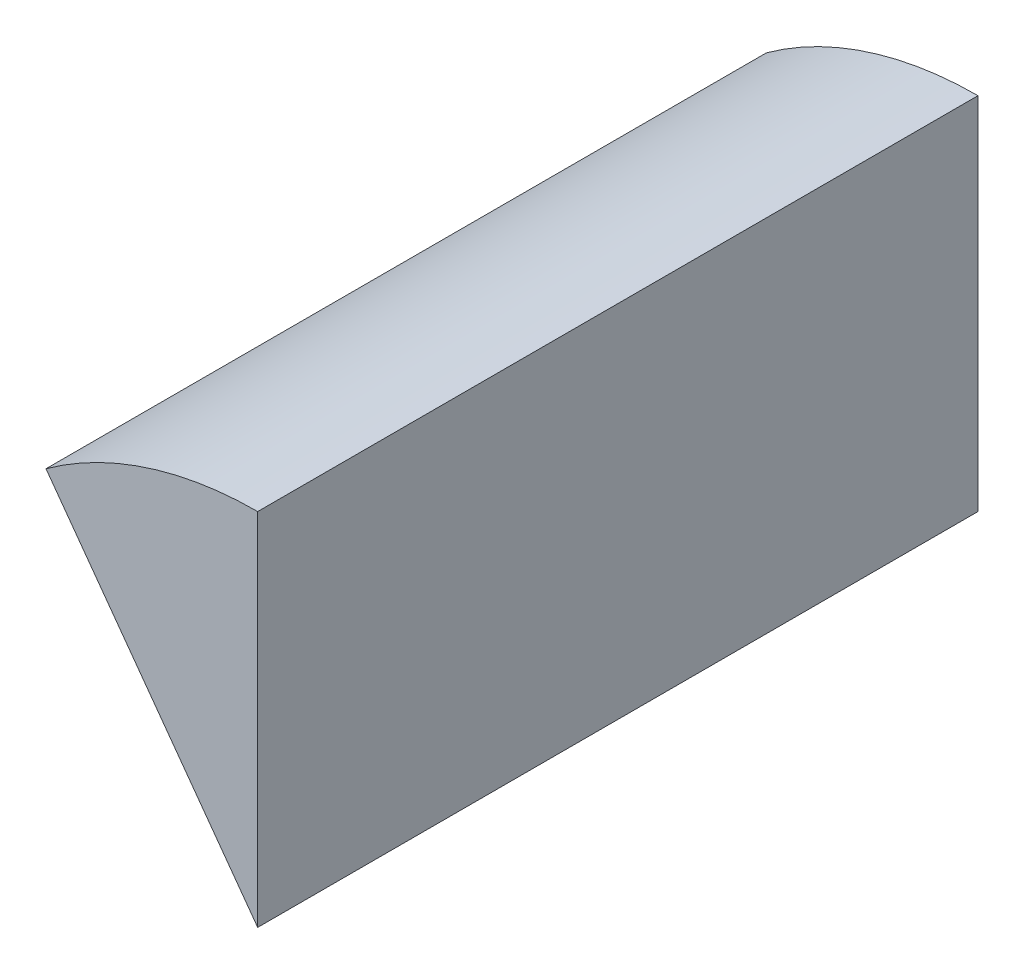
SolidWorks part; units mm, degrees
ref_plane "Alzado" through (0, 0, 0) normal (0, 0, 1) x (1, 0, 0)
ref_plane "Planta" through (0, 0, 0) normal (0, 1, 0) x (1, 0, 0)
ref_plane "Vista lateral" through (0, 0, 0) normal (1, 0, 0) x (0, 0, -1)
sketch "Croquis1" plane through (0, 0, 0) normal (0, 0, 1) x (1, 0, 0)
  line L0 (0, 25) -> (0, 0)
  line L1 (0, 0) -> (-14.6946, 20.2254)
  arc A0 (0, 25) -> (-14.6946, 20.2254) centre (0, 0) ccw
  dimension "D1" = 50
  dimension "D2" = 36
extrude "Saliente-Extruir1" add sketch "Croquis1" along normal blind 50
sketch "Croquis2" plane through (0, 0, 0) normal (0, 0, -1) x (-1, 0, 0)
  circle A0 centre (5.8257, 18.3773) radius 5
  dimension "D1" = 10
extrude "Cortar-Extruir1" cut sketch "Croquis2" against normal blind 10
